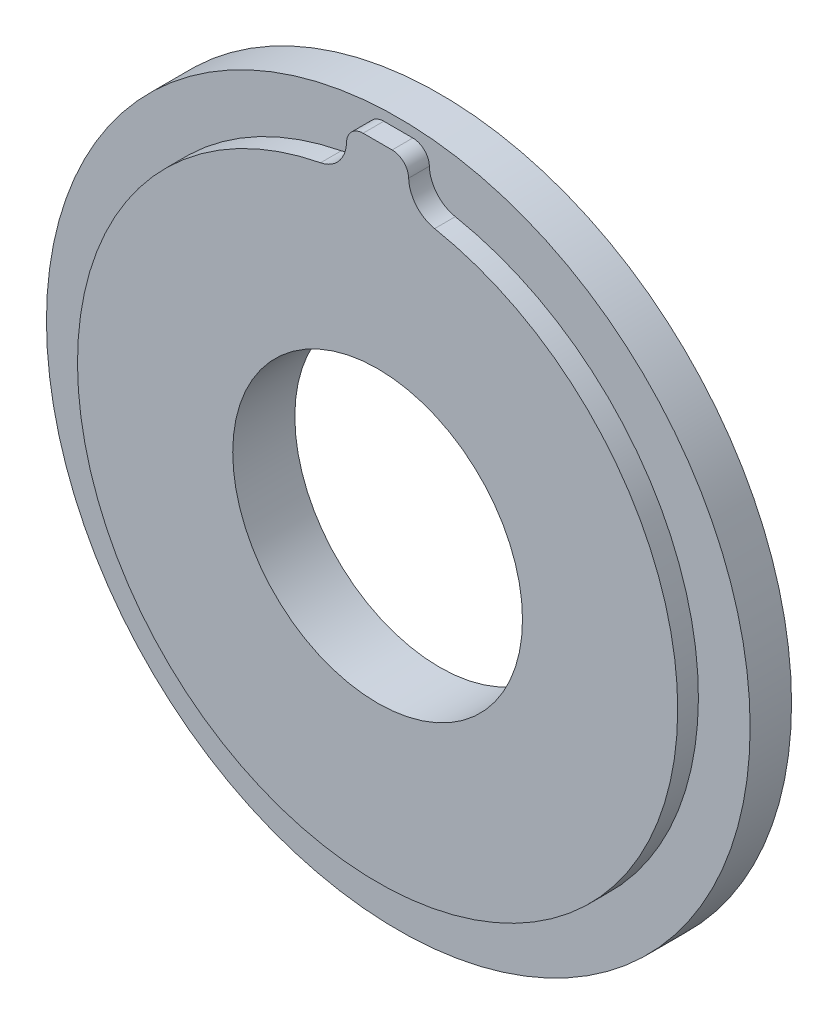
SolidWorks part; units mm, degrees
ref_plane "正面" through (0, 0, 0) normal (0, 0, 1) x (1, 0, 0)
ref_plane "平面" through (0, 0, 0) normal (0, 1, 0) x (1, 0, 0)
ref_plane "右側面" through (0, 0, 0) normal (1, 0, 0) x (0, 0, -1)
sketch "ｽｹｯﾁ1" plane through (0, 0, 0) normal (0, 0, 1) x (1, 0, 0)
  circle A0 centre (0, 0) radius 17
  dimension "D1" = 34
extrude "ﾎﾞｽ - 押し出し1" add sketch "ｽｹｯﾁ1" along normal blind 2
sketch "ｽｹｯﾁ2" plane through (0, 0, 2) normal (0, 0, 1) x (1, 0, 0)
  line L1 (-1.5, 12.5) -> (1.5, 12.5)
  line L2 (-1.5, 12.5) -> (-1.5, 16.5)
  line L3 (-1.5, 16.5) -> (1.5, 16.5)
  line L4 (1.5, 12.5) -> (1.5, 16.5)
  line L5 (-1.5, 12.5) -> (1.5, 16.5) construction
  line L6 (-1.5, 16.5) -> (1.5, 12.5) construction
  circle A0 centre (0, 0) radius 14.5
  point P3 (0, 14.5)
  circle M5 centre (0, 0) radius 17
  dimension "D1" = 29
  dimension "D2" = 2
  dimension "D3" = 3
extrude "ﾎﾞｽ - 押し出し2" add sketch "ｽｹｯﾁ2" along normal blind 1 contours A0 L4 L2 M5 | L4 L3 L2 M5 | L2 A0 L4 L1 | L4 A0 L2 L1
fillet "ﾌｨﾚｯﾄ1" radius 1.55 2 edges at (-1.5, 14.4222, 2.5) (1.5, 14.4222, 2.5)
fillet "ﾌｨﾚｯﾄ2" radius 0.8 2 edges at (1.5, 16.5, 2.5) (-1.5, 16.5, 2.5)
sketch "ｽｹｯﾁ3" plane through (0, 0, 3) normal (0, 0, 1) x (1, 0, 0)
  circle A0 centre (0, 0) radius 7
  dimension "D1" = 14
extrude "ｶｯﾄ - 押し出し1" cut sketch "ｽｹｯﾁ3" against normal through all
sketch "ｽｹｯﾁ4" plane through (0, 0, 0) normal (0, 0, -1) x (-1, 0, 0)
  circle A0 centre (0, 0) radius 12 construction
  circle A1 centre (0, 12) radius 1.25
  circle A2 centre (12, 0) radius 1.25
  circle A3 centre (0, -12) radius 1.25
  circle A4 centre (-12, 0) radius 1.25
  point P14 (0, 0)
  dimension "D1" = 24
  dimension "D2" = 2.5
  dimension "D3" = 4
extrude "ｶｯﾄ - 押し出し2" [suppressed] cut sketch "ｽｹｯﾁ4" against normal through all
